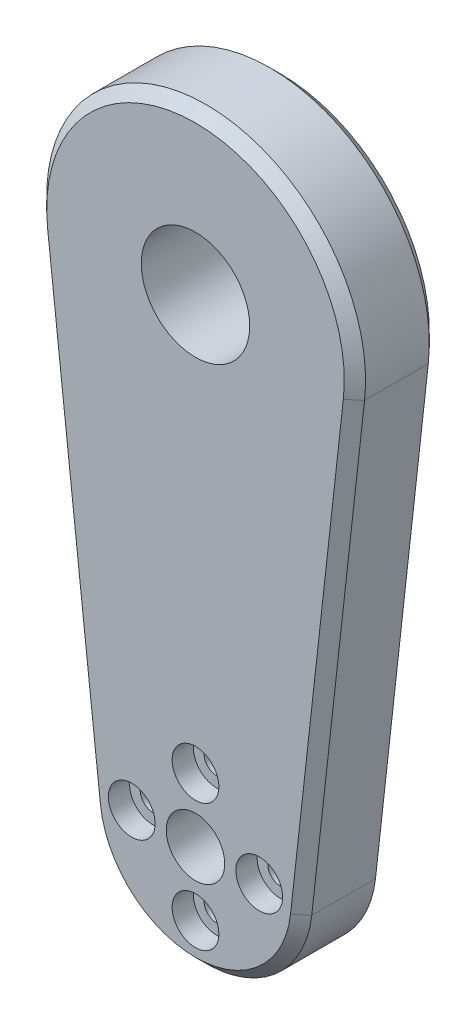
SolidWorks part; units mm, degrees
ref_plane "Front" through (0, 0, 0) normal (0, 0, 1) x (1, 0, 0)
ref_plane "Top" through (0, 0, 0) normal (0, 1, 0) x (1, 0, 0)
ref_plane "Right" through (0, 0, 0) normal (1, 0, 0) x (0, 0, -1)
sketch "Sketch1" plane through (0, 0, 0) normal (0, 0, 1) x (1, 0, 0)
  line L0 (9.9381, -1.1111) -> (14.9071, 43.3333)
  line L1 (0, -50) -> (0, 50) construction
  line L2 (-9.9381, -1.1111) -> (-14.9071, 43.3333)
  arc A0 (-9.9381, -1.1111) -> (9.9381, -1.1111) centre (0, 0) ccw
  arc A1 (14.9071, 43.3333) -> (-14.9071, 43.3333) centre (0, 45) ccw
  circle A2 centre (0, 0) radius 2.75
  circle A3 centre (0, 0) radius 26.4622 construction
  circle A4 centre (0, 45) radius 5.1
  circle A5 centre (0, 45) radius 15 construction
  line B0 (-10, -9.5) -> (10, -9.5) construction
  line B1 (10, -9.5) -> (10, 24.5) construction
  line B2 (10, 24.5) -> (-10, 24.5) construction
  line B3 (-10, 24.5) -> (-10, -9.5) construction
  dimension "D1" = 20
  dimension "D2" = 30
  dimension "D4" = 5.5
  dimension "D5" = 10.2
  dimension "D3" = 45
sketch_block_instance "DYNAMIXEL 330 Front-1"
sketch_block "DYNAMIXEL 330 Front" parameters "D1"=34, "D2"=20, "D3"=30, "D4"=16, "D5"=2, "D6"=2, "D7"=9.5, "D8"=10
extrude "Boss-Extrude1" add sketch "Sketch1" along normal blind 8 contours L0 A1 L2 A0 A2
hole_wizard "CBORE for M2 SHCS1" positions "Sketch2" profile "Sketch3" counterbore size "M2" standard "ANSI Metric" end condition through all
sketch "Sketch2" plane through (0, 0, 8) normal (0, 0, 1) x (1, 0, 0)
  line L0 (0, 0) -> (0, -6) construction
  point P2 (0, -6)
  point P15 (-6, 0)
  point P16 (0, 6)
  point P17 (6, 0)
  point P20 (1.5996, -5.4843)
  point P21 (0, 0)
  dimension "D2" = 6
  dimension "D1" = 4
sketch "Sketch3" plane through (0, -6, 8) normal (1, 0, 0) x (0, -1, 0)
  line L0 (0, 0) -> (0, 8)
  line L1 (0, 8) -> (1.2, 8)
  line L3 (1.2, 8) -> (1.2, 2)
  line L4 (1.2, 2) -> (2.2, 2)
  line L5 (2.2, 2) -> (2.2, 0)
  line L7 (2.2, 0) -> (0, 0)
  line L11 (0, -6.35) -> (0, 107.95) construction
  dimension "Thru Hole Dia." = 2.4
  dimension "Thru Hole Depth" = 8
  dimension "C'Bore Dia." = 4.4
  dimension "C'Bore Depth" = 2
chamfer "Chamfer1" distance 1 angle 45 8 edges at (-12.4226, 21.1111, 8) (0, -10, 8) (0, 60, 8) (12.4226, 21.1111, 8) (-12.4226, 21.1111, 0) (0, -10, 0) (0, 60, 0) (12.4226, 21.1111, 0)
